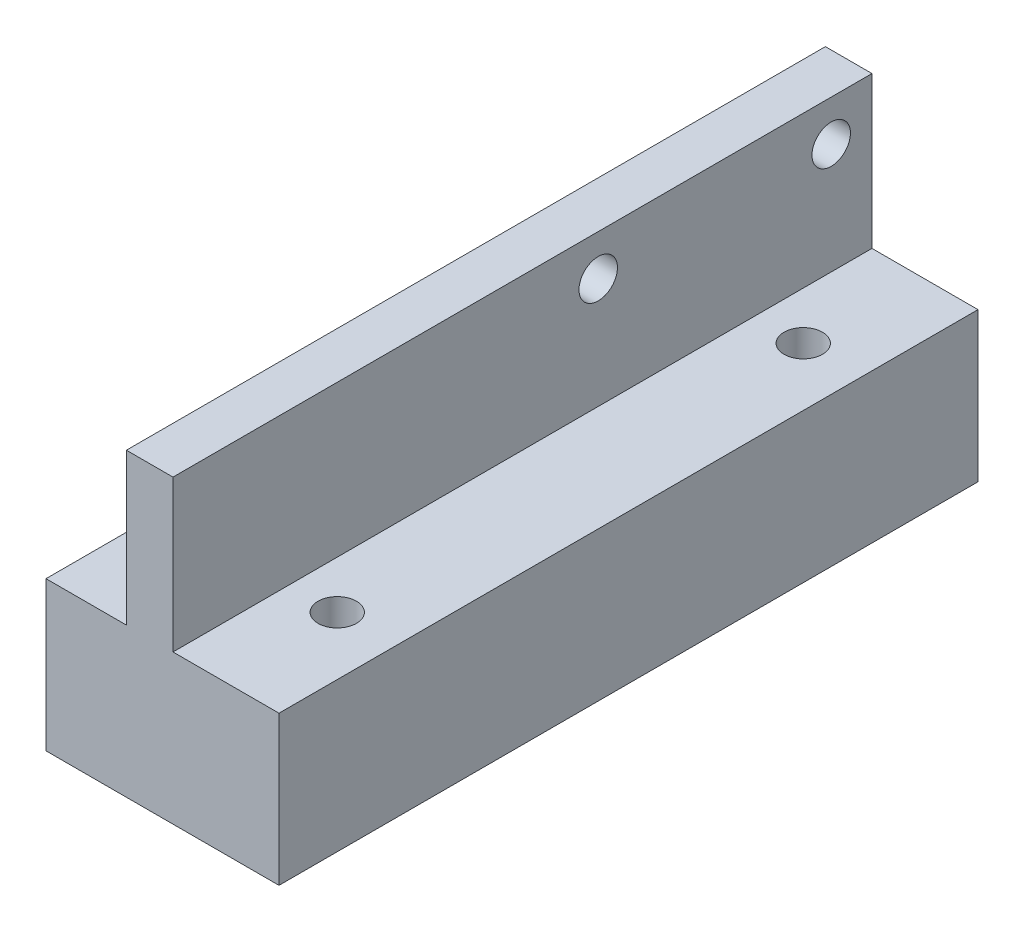
SolidWorks part; units mm, degrees
ref_plane "Front Plane" through (0, 0, 0) normal (0, 0, 1) x (1, 0, 0)
ref_plane "Top Plane" through (0, 0, 0) normal (0, 1, 0) x (1, 0, 0)
ref_plane "Right Plane" through (0, 0, 0) normal (1, 0, 0) x (0, 0, -1)
sketch "Sketch1" plane through (0, 0, 0) normal (0, 1, 0) x (1, 0, 0)
  line L0 (-1.3042, 0) -> (2.0884, 0) construction
  line L1 (0, -3.051) -> (0, -13.887) construction
  line L2 (10, 20) -> (-10, 20) construction
  line L3 (10, -30) -> (-10, -30)
  line L4 (10, -30) -> (10, 30)
  line L5 (10, 30) -> (-10, 30)
  line L6 (-10, -30) -> (-10, 30)
  line L7 (10, -30) -> (-10, 30) construction
  line L8 (10, 30) -> (-10, -30) construction
  line L9 (10, -20) -> (-10, -20) construction
  circle A6 centre (5, 20) radius 1.65
  circle A7 centre (5, -20) radius 1.65
  point P3 (0, 0)
  point P17 (0, 0)
  dimension "D4" = 3.3
  dimension "D1" = 10
  dimension "D2" = 40
  dimension "D3" = 20
  dimension "D5" = 5
extrude "Boss-Extrude1" add sketch "Sketch1" along normal blind 12.8
sketch "Sketch2" plane through (0, 12.8, 0) normal (0, 1, 0) x (1, 0, 0)
  line L5 (10, 30) -> (-10, 30) construction
  line L6 (0.9, 30) -> (-3.1, 30)
  line L7 (0.9, 30) -> (0.9, -30)
  line L8 (0.9, -30) -> (-3.1, -30)
  line L9 (-3.1, 30) -> (-3.1, -30)
  line L10 (-10, -30) -> (10, -30) construction
  line L11 (10, -30) -> (10, 30) construction
  dimension "D1" = 13.1
  dimension "D2" = 4
extrude "Boss-Extrude3" add sketch "Sketch2" along normal blind 13
sketch "Sketch3" plane through (0.9, 0, 0) normal (1, 0, 0) x (0, 0, -1)
  line L0 (-30, 22.3) -> (30, 22.3) construction
  line L1 (-30, 25.8) -> (-30, 12.8) construction
  line L2 (30, 25.8) -> (30, 12.8) construction
  line L5 (-30, 25.8) -> (30, 25.8) construction
  circle A0 centre (6.5, 22.3) radius 1.65
  circle A1 centre (26.5, 22.3) radius 1.65
  point P12 (4.7709, 15.5)
  dimension "D2" = 3.3
  dimension "D1" = 3.5
  dimension "D3" = 20
  dimension "D4" = 3.5
extrude "Cut-Extrude1" cut sketch "Sketch3" against normal up to surface (4 mm away) up to face at (-3.1, 19.3, 0)
